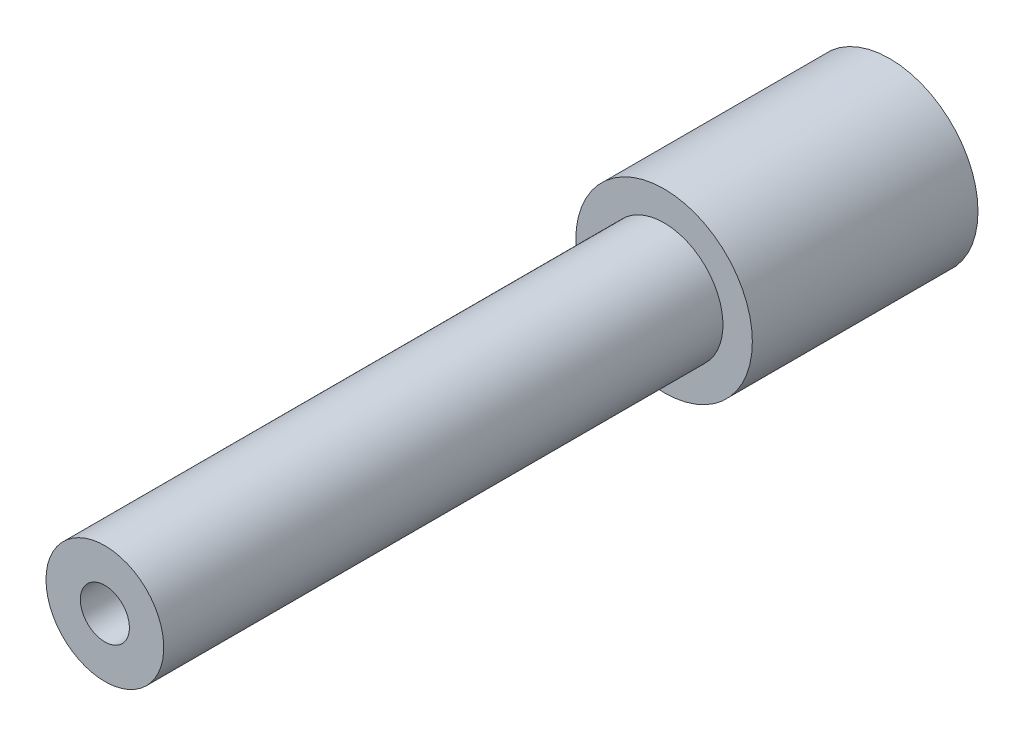
SolidWorks part; units mm, degrees
ref_plane "Front Plane" through (0, 0, 0) normal (0, 0, 1) x (1, 0, 0)
ref_plane "Top Plane" through (0, 0, 0) normal (0, 1, 0) x (1, 0, 0)
ref_plane "Right Plane" through (0, 0, 0) normal (1, 0, 0) x (0, 0, -1)
sketch "Sketch1" plane through (0, 0, 0) normal (0, 0, 1) x (1, 0, 0)
  circle A0 centre (0, 0) radius 4.5
  dimension "D1" = 9
extrude "Boss-Extrude2" add sketch "Sketch1" along normal blind 11.5
sketch "Sketch16" plane through (0, 0, 11.5) normal (0, 0, 1) x (1, 0, 0)
  circle A0 centre (0, 0) radius 3
  dimension "D1" = 6
extrude "Boss-Extrude3" add sketch "Sketch16" along normal blind 28.5
sketch "Sketch17" plane through (0, 0, 40) normal (0, 0, 1) x (1, 0, 0)
  circle A0 centre (0, 0) radius 1.25
  dimension "D1" = 2.5
extrude "Cut-Extrude1" cut sketch "Sketch17" against normal blind 7
